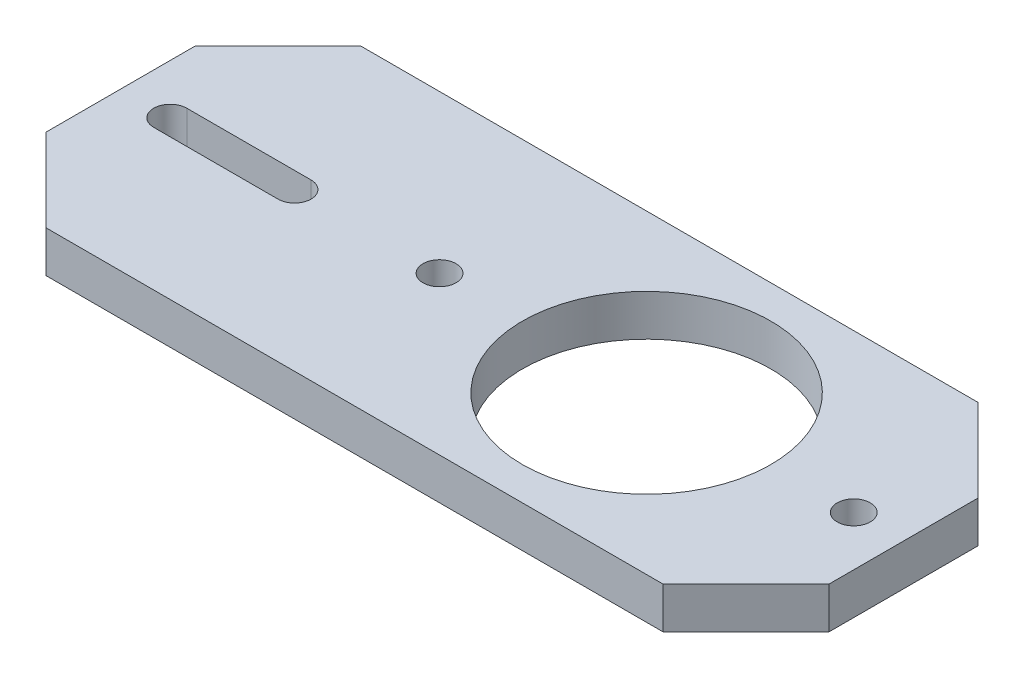
SolidWorks part; units mm, degrees
material "Pine"
ref_plane "Front Plane" through (0, 0, 0) normal (0, 0, 1) x (1, 0, 0)
ref_plane "Top Plane" through (0, 0, 0) normal (0, 1, 0) x (1, 0, 0)
ref_plane "Right Plane" through (0, 0, 0) normal (1, 0, 0) x (0, 0, -1)
sketch "Sketch1" plane through (0, 0, 0) normal (0, 1, 0) x (1, 0, 0)
  line L0 (-57.5, 2) -> (-42.5, 2)
  line L1 (-57.5, -2) -> (-42.5, -2)
  line L2 (-84.5376, 0) -> (67.9764, 0) construction
  line L3 (-50, 2) -> (-50, -2) construction
  line L4 (-63.5, 9) -> (-53.5, 19)
  line L5 (-53.5, 19) -> (21, 19)
  line L6 (-63.5, 9) -> (-63.5, -9)
  line L7 (-53.5, -19) -> (21, -19)
  line L8 (31, 9) -> (31, -9)
  line L9 (-63.5, -9) -> (-53.5, -19)
  line L10 (21, -19) -> (31, -9)
  line L11 (21, 19) -> (31, 9)
  circle A0 centre (-25, 0) radius 2
  circle A1 centre (25, 0) radius 2
  arc A2 (-42.5, -2) -> (-42.5, 2) centre (-42.5, 0) ccw
  arc A4 (-57.5, 2) -> (-57.5, -2) centre (-57.5, 0) ccw
  circle A5 centre (0, 0) radius 15
  point P19 (-63.5, 19)
  point P20 (31, -19)
  point P21 (-63.5, -19)
  point P22 (31, 19)
  dimension "D1" = 4
  dimension "D2" = 4
  dimension "D4" = 4
  dimension "D5" = 75
  dimension "D8" = 4
  dimension "D10" = 30
  dimension "D12" = 6
  dimension "D3" = 50
  dimension "D6" = 15
  dimension "D7" = 6
  dimension "D11" = 25
  dimension "D14" = 19
  dimension "D15" = 19
extrude "Boss-Extrude1" add sketch "Sketch1" against normal blind 5
equation "\"rod_diameter\"= 8"
equation "\"rod_hole_thickness\"= 4"
equation "\"rod_radius\"= \"rod_diameter\" / 2"
equation "\"platter_diameter\"= 320"
equation "\"platter_radius\"= \"platter_diameter\" / 2"
equation "\"extruder_mount_hole_spacing\"= 75"
equation "\"arm_rod_spacing\"= 40"
equation "\"top_frame_rod_spacing\"= \"arm_rod_spacing\" + 40"
equation "\"motor_level_rod_spacing\"= 15"
equation "\"linear_bearing_diameter\"= 15"
equation "\"z_rod_spacing\"= 75"
equation "\"platter_rod_spacing\"= 50"
equation "\"rod_nut_thickness\"= 6.5"
equation "\"rod_nut_inscribed_diameter\"= 13"
equation "\"z_height\"= 350"
equation "\"gear_pitch\"=2"
equation "\"r_gear_teeth\"= 450"
equation "\"theta_gear_teeth\"= 385"
equation "\"D12@Sketch1\"=2 + \"rod_hole_thickness\""
equation "\"D14@Sketch1\"=15 +\"rod_hole_thickness\""
equation "\"D15@Sketch1\" = 15 + \"rod_hole_thickness\""
equation "\"D7@Sketch1\"=\"rod_hole_thickness\"+2"
equation "\"D5@Sketch1\"=\"extruder_mount_hole_spacing\""
